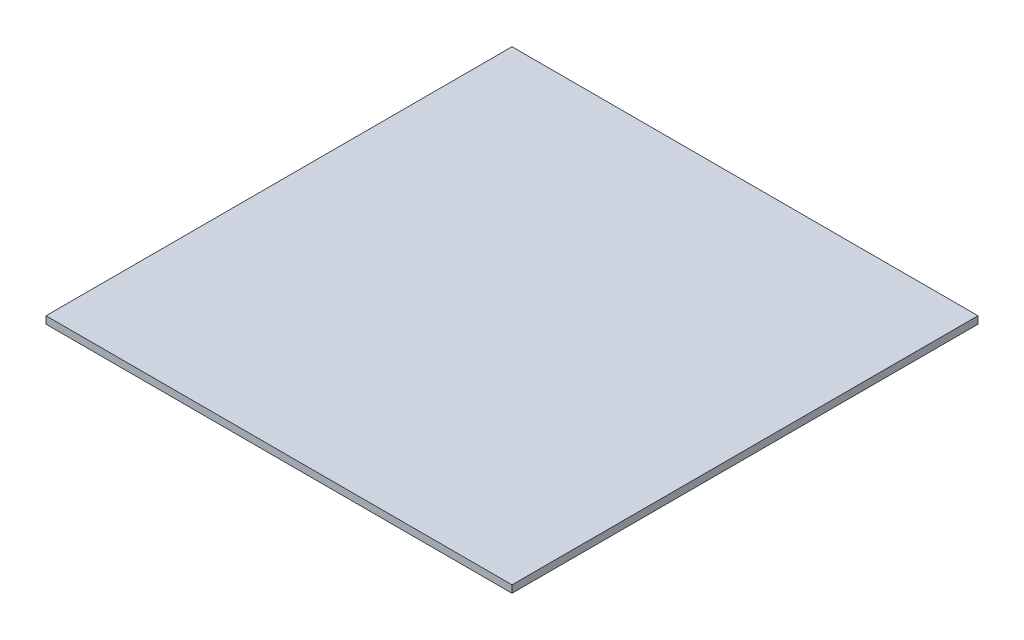
SolidWorks part; units mm, degrees
ref_plane "Front Plane" through (0, 0, 0) normal (0, 0, 1) x (1, 0, 0)
ref_plane "Top Plane" through (0, 0, 0) normal (0, 1, 0) x (1, 0, 0)
ref_plane "Right Plane" through (0, 0, 0) normal (1, 0, 0) x (0, 0, -1)
sketch "Sketch1" plane through (0, 0, 0) normal (0, 1, 0) x (1, 0, 0)
  line L1 (-31.75, -31.75) -> (31.75, -31.75)
  line L2 (-31.75, -31.75) -> (-31.75, 31.75)
  line L3 (-31.75, 31.75) -> (31.75, 31.75)
  line L4 (31.75, -31.75) -> (31.75, 31.75)
  line L5 (-31.75, -31.75) -> (31.75, 31.75) construction
  line L6 (-31.75, 31.75) -> (31.75, -31.75) construction
  point P0 (0, 0)
  dimension "D1" = 63.5
extrude "Boss-Extrude1" add sketch "Sketch1" along normal blind 1
